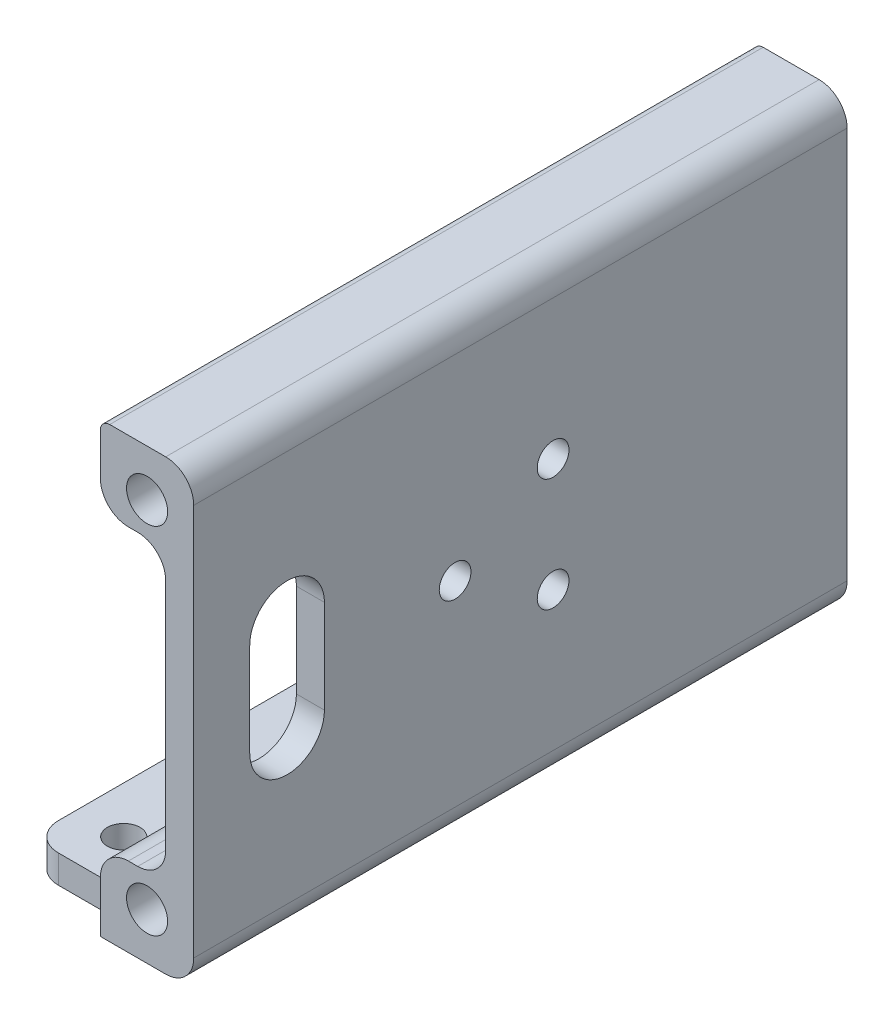
SolidWorks part; units mm, degrees
ref_plane "Front Plane" through (0, 0, 0) normal (0, 0, 1) x (1, 0, 0)
ref_plane "Top Plane" through (0, 0, 0) normal (0, 1, 0) x (1, 0, 0)
ref_plane "Right Plane" through (0, 0, 0) normal (1, 0, 0) x (0, 0, -1)
sketch "Sketch1" plane through (0, 0, 0) normal (0, 0, 1) x (1, 0, 0)
  line L0 (54, -19) -> (54, 19) construction
  line L1 (49, 24) -> (49, 18.5)
  line L2 (49, 24) -> (56, 24)
  line L4 (49, -24) -> (56, -24)
  line L5 (59, 21) -> (59, -21)
  line L6 (49, 24) -> (59, -24) construction
  line L7 (49, -24) -> (59, 24) construction
  line L8 (52, 15.5) -> (53, 15.5)
  line L9 (56, 12.5) -> (56, -12.5)
  line L10 (53, -15.5) -> (52, -15.5)
  line L11 (49, -18.5) -> (49, -24)
  arc A0 (56, -24) -> (59, -21) centre (56, -21) ccw
  arc A1 (59, 21) -> (56, 24) centre (56, 21) ccw
  arc A2 (56, -12.5) -> (53, -15.5) centre (53, -12.5) cw
  arc A3 (56, 12.5) -> (53, 15.5) centre (53, 12.5) ccw
  arc A4 (52, -15.5) -> (49, -18.5) centre (52, -18.5) ccw
  arc A5 (52, 15.5) -> (49, 18.5) centre (52, 18.5) cw
  point P4 (54, 0)
  dimension "D3" = 3
  dimension "D4" = 3
  dimension "D5" = 3
  dimension "D6" = 3
  dimension "D1" = 10
  dimension "D2" = 48
  dimension "D7" = 7
  dimension "D8" = 5.5
extrude "Boss-Extrude1" add sketch "Sketch1" along normal blind 70
sketch "Sketch2" plane through (0, 0, 0) normal (0, 0, -1) x (-1, 0, 0)
  circle A0 centre (-54, -19) radius 2.2
  circle A1 centre (-54, 19) radius 2.2
  dimension "D1" = 4.4
ref_plane "Plane1" through (0, 0, 35) normal (0, 0, -1) x (-1, 0, 0)
extrude "Cut-Extrude1" cut sketch "Sketch2" against normal blind 5.3
mirror "Mirror1" about plane through (0, 0, 35) normal (0, 0, -1) of "Cut-Extrude1"
fillet "Fillet1" radius 1 1 edges at (49, 24, 35)
sketch "Sketch4" plane through (59, 0, 0) normal (1, 0, 0) x (0, 0, -1)
  line L0 (-42, 0) -> (-35, 0) construction
  line L1 (-35, 0) -> (-31.5, 6.0622) construction
  line L2 (-35, 0) -> (-31.5, -6.0622) construction
  line L3 (-60, -5) -> (-60, 5) construction
  line L4 (-70, 0) -> (-35, 0) construction
  line L5 (-70, -21) -> (-70, 21) construction
  line L6 (-64, -5) -> (-64, 5)
  line L7 (-56, -5) -> (-56, 5)
  circle A0 centre (-42, 0) radius 1.7
  circle A1 centre (-31.5, 6.0622) radius 1.7
  circle A2 centre (-31.5, -6.0622) radius 1.7
  circle A3 centre (-35, 0) radius 7 construction
  arc A5 (-64, -5) -> (-56, -5) centre (-60, -5) ccw
  arc A6 (-56, 5) -> (-64, 5) centre (-60, 5) ccw
  point P15 (-60, 0)
  dimension "D1" = 14
  dimension "D2" = 3.4
  dimension "D6" = 4
  dimension "D7" = 10
  dimension "D3" = 120
  dimension "D4" = 120
  dimension "D5" = 35
extrude "Cut-Extrude3" cut sketch "Sketch4" against normal blind 10
sketch "Sketch5" plane through (0, -24, 0) normal (0, -1, 0) x (1, 0, 0)
  line L0 (49, 35) -> (39, 35) construction
  line L1 (49, 70) -> (49, 0) construction
  line L2 (44, 35) -> (44, 62.5) construction
  line L3 (49, 2.5) -> (42, 2.5)
  line L4 (49, 2.5) -> (49, 67.5)
  line L5 (49, 67.5) -> (42, 67.5)
  line L6 (39, 5.5) -> (39, 64.5)
  line L7 (49, 2.5) -> (39, 67.5) construction
  line L8 (49, 67.5) -> (39, 2.5) construction
  arc A0 (39, 5.5) -> (42, 2.5) centre (42, 5.5) ccw
  arc A1 (39, 64.5) -> (42, 67.5) centre (42, 64.5) cw
  circle A2 centre (44, 62.5) radius 1.75
  circle A3 centre (44, 7.5) radius 1.75
  point P4 (44, 35)
  dimension "D3" = 3
  dimension "D5" = 3.5
  dimension "D1" = 65
  dimension "D2" = 10
  dimension "D4" = 5
extrude "Boss-Extrude2" add sketch "Sketch5" against normal blind 3
chamfer "Chamfer1" distance 1 angle 45 3 edges at (49, -22.5, 2.5) (49, -21, 35) (49, -22.5, 67.5)
